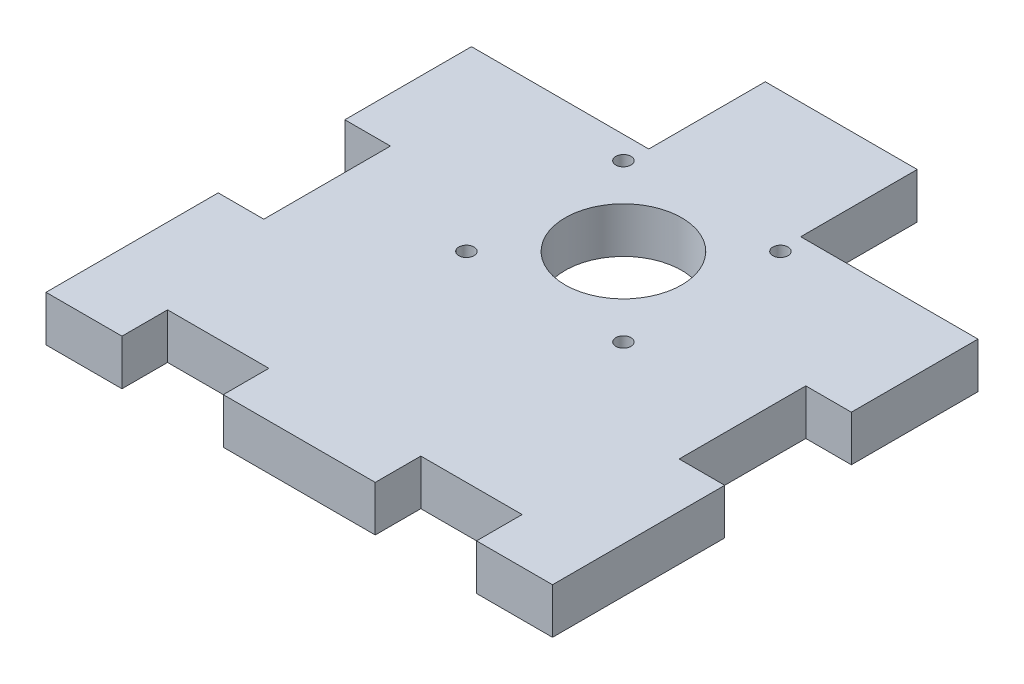
SolidWorks part; units mm, degrees
ref_plane "Front Plane" through (0, 0, 0) normal (0, 0, 1) x (1, 0, 0)
ref_plane "Top Plane" through (0, 0, 0) normal (0, 1, 0) x (1, 0, 0)
ref_plane "Right Plane" through (0, 0, 0) normal (1, 0, 0) x (0, 0, -1)
sketch "Sketch2" plane through (0, 0, 0) normal (0, 1, 0) x (1, 0, 0)
  line L0 (0, 37.5) -> (0, -37.5) construction
  line L1 (-50, 37.5) -> (50, 37.5)
  line L2 (-50, 37.5) -> (-50, -37.5)
  line L3 (-50, -37.5) -> (50, -37.5)
  line L4 (50, 37.5) -> (50, -37.5)
  line L5 (-50, 37.5) -> (50, -37.5) construction
  line L6 (-50, -37.5) -> (50, 37.5) construction
  line L7 (35, 37.5) -> (35, 46.5)
  line L8 (-50, 37.5) -> (-35, 37.5)
  line L9 (-50, 37.5) -> (-50, 46.5)
  line L10 (-50, 46.5) -> (-35, 46.5)
  line L11 (-35, 37.5) -> (-35, 46.5)
  line L12 (-15, 37.5) -> (15, 37.5)
  line L13 (-15, 37.5) -> (-15, 46.5)
  line L15 (15, 37.5) -> (15, 46.5)
  line L16 (50, 46.5) -> (35, 46.5)
  line L17 (50, 37.5) -> (50, 46.5)
  line L18 (50, 37.5) -> (35, 37.5)
  line L19 (-50, 0) -> (47.6248, 0) construction
  line L20 (50, -37.5) -> (35, -37.5)
  line L21 (50, -37.5) -> (50, -46.5)
  line L22 (50, -46.5) -> (35, -46.5)
  line L23 (15, -37.5) -> (15, -46.5)
  line L24 (-15, -46.5) -> (15, -46.5)
  line L25 (-15, -37.5) -> (-15, -46.5)
  line L26 (-15, -37.5) -> (15, -37.5)
  line L27 (-35, -37.5) -> (-35, -46.5)
  line L28 (-50, -46.5) -> (-35, -46.5)
  line L29 (-50, -37.5) -> (-50, -46.5)
  line L30 (-50, -37.5) -> (-35, -37.5)
  line L31 (35, -37.5) -> (35, -46.5)
  line L32 (-50, -37.5) -> (50, -37.5)
  line L34 (-15, 46.5) -> (-15, 60.5)
  line L35 (-15, 60.5) -> (15, 60.5)
  line L36 (15, 46.5) -> (15, 60.5)
  circle A0 centre (-29, 17.5) radius 4
  circle A1 centre (29, 17.5) radius 4
  point P0 (0, 0)
  dimension "D3" = 8
  dimension "D10" = 14
  dimension "D1" = 75
  dimension "D2" = 100
  dimension "D4" = 20
  dimension "D5" = 21
  dimension "D6" = 15
  dimension "D7" = 9
  dimension "D8" = 20
  dimension "D9" = 30
extrude "Boss-Extrude1" add sketch "Sketch2" along normal blind 9
sketch "Sketch4" plane through (0, 9, 0) normal (0, 1, 0) x (1, 0, 0)
  line L0 (-50, 37.5) -> (50, 37.5) construction
  line L1 (0, 33) -> (0, 2) construction
  line L2 (-15.5, 33) -> (15.5, 33)
  line L3 (-15.5, 33) -> (-15.5, 2)
  line L4 (-15.5, 2) -> (15.5, 2)
  line L5 (15.5, 33) -> (15.5, 2)
  line L6 (-15.5, 33) -> (15.5, 2) construction
  line L7 (-15.5, 2) -> (15.5, 33) construction
  line L8 (-15.5, 17.5) -> (15.5, 17.5) construction
  circle A0 centre (0, 17.5) radius 11.5
  circle A1 centre (15.5, 33) radius 1.5
  circle A2 centre (-15.5, 33) radius 1.5
  circle A3 centre (-15.5, 2) radius 1.5
  circle A4 centre (15.5, 2) radius 1.5
  dimension "D2" = 23
  dimension "D4" = 3
  dimension "D1" = 20
  dimension "D3" = 31
  dimension "D5" = 31
extrude "Cut-Extrude1" cut sketch "Sketch4" against normal through all contours A0 | A3 | A4 | A1 | A2
sketch "Sketch5" plane through (0, 9, 0) normal (0, 1, 0) x (1, 0, 0)
  line L0 (-50, 46.5) -> (-50, -46.5) construction
  line L1 (-50, 12.5) -> (-41, 12.5)
  line L2 (50, -12.5) -> (49.8078, -12.77)
  line L3 (-50, -12.5) -> (-41, -12.5)
  line L4 (-41, 12.5) -> (-41, -12.5)
  line L5 (-50, 12.5) -> (-50, -12.5)
  line L6 (-50, -12.5) -> (-49.8078, -12.77)
  line L7 (50, 12.5) -> (50, -12.5)
  line L8 (0, 0) -> (0, 46.5) construction
  line L10 (41, 12.5) -> (41, -12.5)
  line L11 (50, 46.5) -> (50, -46.5) construction
  line L12 (50, -12.5) -> (41, -12.5)
  line L13 (50, 12.5) -> (41, 12.5)
  line L14 (-15, -46.5) -> (15, -46.5) construction
  line L17 (-41, 0) -> (50, 0) construction
  line M7 (50, -46.5) -> (50, 46.5)
  line M17 (-50, 46.5) -> (-50, -46.5)
  dimension "D1" = 25
  dimension "D2" = 9
  dimension "D3" = 12.5
  dimension "D4" = 46.5
extrude "Cut-Extrude2" cut sketch "Sketch5" against normal through all contours L4 L1 L3 M17 | L13 L10 L12 M7
sketch "Sketch6" plane through (0, 9, 0) normal (0, 1, 0) x (1, 0, 0)
  line L0 (50, 46.5) -> (50, 12.5) construction
  line L1 (-50, 46.5) -> (-35, 46.5)
  line L2 (-50, 46.5) -> (-50, 37.5)
  line L3 (-50, 37.5) -> (-35, 37.5)
  line L4 (-35, 46.5) -> (-35, 37.5)
  line L5 (35, 46.5) -> (50, 46.5)
  line L6 (35, 46.5) -> (35, 37.5)
  line L7 (35, 37.5) -> (50, 37.5)
  line L8 (50, 46.5) -> (50, 37.5)
extrude "Cut-Extrude3" cut sketch "Sketch6" against normal through all
